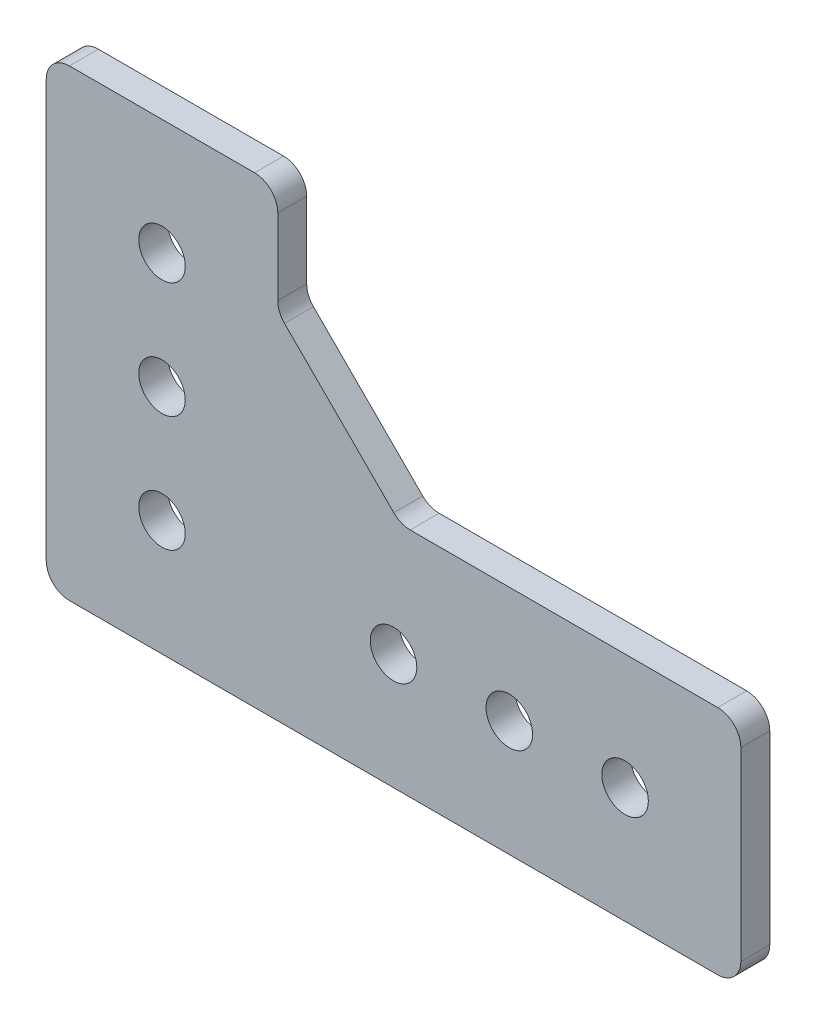
SolidWorks part; units mm, degrees
material "6061 Alloy"
ref_plane "Front" through (0, 0, 0) normal (0, 0, 1) x (1, 0, 0)
ref_plane "Top" through (0, 0, 0) normal (0, 1, 0) x (1, 0, 0)
ref_plane "Right" through (0, 0, 0) normal (1, 0, 0) x (0, 0, -1)
sketch "Sketch1" plane through (0, 0, 0) normal (0, 0, 1) x (1, 0, 0)
  line L1 (0, 0) -> (-76.2, 0)
  line L2 (0, 0) -> (0, 25.4)
  line L3 (0, 25.4) -> (-37.3296, 25.4)
  line L4 (-76.2, 0) -> (-76.2, 50.8)
  line L7 (-76.2, 50.8) -> (-50.8, 50.8)
  line L8 (-50.8, 38.8704) -> (-50.8, 50.8)
  line L9 (-50.8, 38.8704) -> (-37.3296, 25.4)
  dimension "D1" = 76.2
  dimension "D2" = 50.8
  dimension "D3" = 19.05
  dimension "D4" = 135
  dimension "D5" = 25.4
  dimension "D6" = 25.4
extrude "Boss-Extrude1" add sketch "Sketch1" along normal blind 3.175 contours L3 L8 L7 L4 L1 L2
hole_wizard "#10 Clearance Hole1" positions "Sketch2" profile "Sketch3" hole size "#10" standard "ANSI Inch"
sketch "Sketch2" plane through (0, 0, 3.175) normal (0, 0, 1) x (1, 0, 0)
  line L0 (0, 0) -> (-76.2, 0) construction
  line L2 (0, 25.4) -> (-37.3296, 25.4) construction
  line L3 (-76.2, 0) -> (-76.2, 50.8) construction
  point P0 (-63.5, 38.1)
  point P2 (-63.5, 25.4)
  point P4 (-63.5, 12.7)
  point P6 (-38.1, 12.7)
  point P8 (-25.4, 12.7)
  point P17 (-12.7, 12.7)
  dimension "D1" = 12.7
  dimension "D2" = 12.7
  dimension "D3" = 12.7
  dimension "D4" = 12.7
  dimension "D5" = 12.7
  dimension "D6" = 38.1
  dimension "D7" = 12.7
sketch "Sketch3" plane through (-63.5, 38.1, 3.175) normal (1, 0, 0) x (0, -1, 0)
  line L0 (0, 0) -> (0, 4.7078)
  line L1 (0, 4.7078) -> (2.5527, 3.174)
  line L2 (2.5527, 3.174) -> (2.5527, 0)
  line L5 (2.5527, 0) -> (0, 0)
  line L10 (0, 4.7078) -> (-2.5527, 3.174) construction
  line L11 (0, -6.35) -> (0, 107.95) construction
  dimension "Hole Dia." = 5.1054
  dimension "Hole Depth" = 3.174
  dimension "Drill Angle" = 118
fillet "Fillet1" radius 2.54 7 edges at (0, 0, 1.5875) (-76.2, 0, 1.5875) (-76.2, 50.8, 1.5875) (-50.8, 50.8, 1.5875) (-50.8, 38.8704, 1.5875) (-37.3296, 25.4, 1.5875) (0, 25.4, 1.5875)
